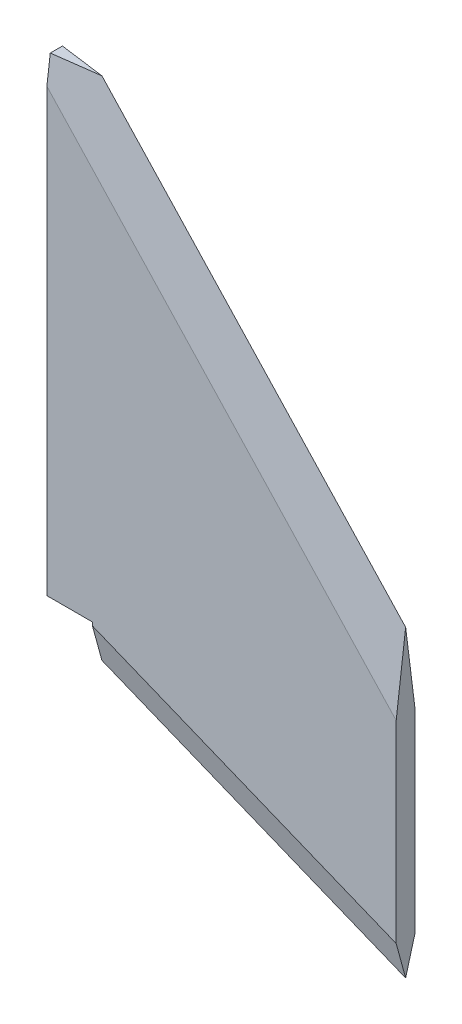
SolidWorks part; units mm, degrees
ref_plane "Front Plane" through (0, 0, 0) normal (0, 0, 1) x (1, 0, 0)
ref_plane "Top Plane" through (0, 0, 0) normal (0, 1, 0) x (1, 0, 0)
ref_plane "Right Plane" through (0, 0, 0) normal (1, 0, 0) x (0, 0, -1)
sketch "Sketch2" plane through (0, 0, 0) normal (0, 0, 1) x (1, 0, 0)
  line L0 (0, 0) -> (0, 127)
  line L1 (0, 127) -> (76.2, 45.2882)
  line L2 (76.2, 45.2882) -> (76.2, -30.9118)
  line L3 (76.2, -30.9118) -> (0, 0)
  line L9 (0, 127) -> (-11.43, 127)
  line L10 (0, 127) -> (0, 9.525)
  line L11 (0, 9.525) -> (-11.43, 9.525)
  line L12 (-11.43, 127) -> (-11.43, 9.525)
  dimension "D1" = 127
  dimension "D2" = 76.2
  dimension "D3" = 76.2
  dimension "D4" = 81.7118
  dimension "D5" = 11.43
  dimension "D6" = 117.475
extrude "Boss-Extrude3" add sketch "Sketch2" along normal blind 4.7498 contours L3 L2 L1 L0 | L10 L9 L12 L11
ref_plane "Plane3" through (12.8545, -13.7843, 0) normal (0.682, -0.7313, 0) x (0, 0, -1)
ref_plane "Plane4" through (0, 0, 0) normal (-0.9267, 0.3759, 0) x (0, 0, -1)
sketch "Sketch8" plane through (0, 0, 0) normal (-0.9267, 0.3759, 0) x (0, 0, -1)
  line L0 (-2.3749, 0) -> (0, -8.0385)
  line L1 (-4.7498, 0) -> (0, 0) construction
  line L2 (-2.3749, 0) -> (-4.7498, -8.0385)
  line L3 (-4.7498, -8.0385) -> (-5.3143, -8.0385)
  line L4 (-5.3143, -8.0385) -> (-5.3143, 2.3102)
  line L5 (-5.3143, 2.3102) -> (0.7503, 2.3102)
  line L6 (0.7503, 2.3102) -> (0.7503, -8.0385)
  line L7 (0.7503, -8.0385) -> (0, -8.0385)
  dimension "D1" = 4.7498
  dimension "D2" = 8.382
  dimension "D3" = 32.918
extrude "Cut-Extrude17" cut sketch "Sketch8" against normal blind 101.6 and the other way blind 5.08 contours L4 L5 L6 L7 L0 L2 L3
sketch "Sketch9" plane through (12.8545, -13.7843, 0) normal (0.682, -0.7313, 0) x (0, 0, -1)
  line L0 (-2.3749, 86.6153) -> (0, 73.6226)
  line L1 (-4.7498, 86.6153) -> (0, 86.6153) construction
  line L2 (0, 86.6153) -> (0, 40.5624) construction
  line L3 (-2.3749, 86.6153) -> (-4.7498, 73.6226)
  line L4 (-4.7498, 86.6153) -> (-4.7498, 40.5624) construction
  line L5 (-4.7498, 73.6226) -> (-6.5312, 73.6226)
  line L6 (-6.5312, 73.6226) -> (-6.5312, 91.3015)
  line L7 (-6.5312, 91.3015) -> (0.8726, 91.3015)
  line L8 (0.8726, 91.3015) -> (0.8726, 73.6226)
  line L9 (0.8726, 73.6226) -> (0, 73.6226)
  dimension "D1" = 13.208
  dimension "D2" = 4.7498
  dimension "D3" = 20.717
extrude "Cut-Extrude18" cut sketch "Sketch9" against normal blind 127 and the other way blind 101.6
